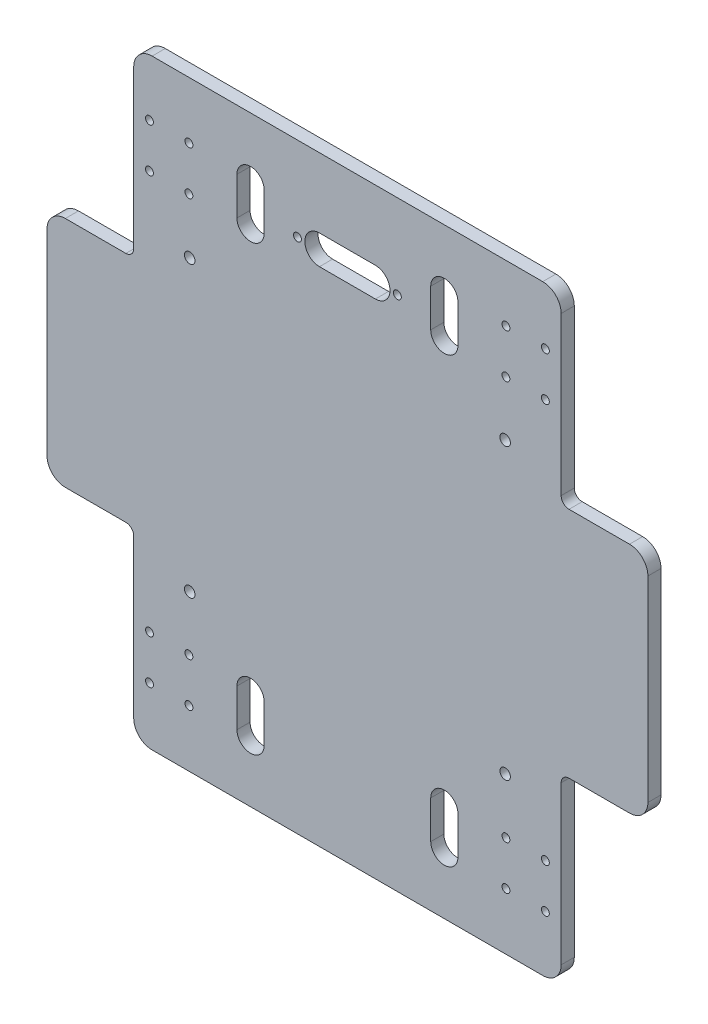
SolidWorks part; units mm, degrees
ref_plane "Front Plane" through (0, 0, 0) normal (0, 0, 1) x (1, 0, 0)
ref_plane "Top Plane" through (0, 0, 0) normal (0, 1, 0) x (1, 0, 0)
ref_plane "Right Plane" through (0, 0, 0) normal (1, 0, 0) x (0, 0, -1)
sketch "Sketch1" plane through (0, 0, 0) normal (0, 0, 1) x (1, 0, 0)
  line L0 (33, -6.6196) -> (39, -6.6196) construction
  line L1 (33, 0) -> (195.6, 0)
  line L2 (0, -70) -> (0, -158.6)
  line L3 (33, -228.6) -> (195.6, -228.6)
  line L4 (228.6, -70) -> (228.6, -158.6)
  line L5 (0, -70) -> (33, -70)
  line L6 (77.4385, -191.4014) -> (77.4385, -205.7986) construction
  line L11 (39, -30) -> (54, -30) construction
  line L12 (33, -70) -> (33, 0)
  line L13 (0, -158.6) -> (33, -158.6)
  line L14 (33, -158.6) -> (33, -228.6)
  line L15 (195.6, -158.6) -> (195.6, -228.6)
  line L16 (228.6, -158.6) -> (195.6, -158.6)
  line L17 (228.6, -70) -> (195.6, -70)
  line L18 (195.6, -70) -> (195.6, 0)
  line L19 (39, -30) -> (39, -38.375) construction
  line L20 (77.4385, -37.1986) -> (77.4385, -22.8014) construction
  line L21 (72.2648, -37.1986) -> (72.2648, -22.8014)
  line L22 (82.6122, -37.1986) -> (82.6122, -22.8014)
  line L23 (103.6573, -32) -> (124.9427, -32) construction
  line L24 (103.6573, -26.4466) -> (124.9427, -26.4466)
  line L25 (103.6573, -37.5534) -> (124.9427, -37.5534)
  line L26 (114.3, 0) -> (114.3, -14.4464) construction
  line L27 (0, -114.3) -> (33, -114.3) construction
  line L28 (72.2648, -191.4014) -> (72.2648, -205.7986)
  line L29 (82.6122, -191.4014) -> (82.6122, -205.7986)
  line L30 (151.1615, -191.4014) -> (151.1615, -205.7986) construction
  line L31 (156.3352, -191.4014) -> (156.3352, -205.7986)
  line L32 (145.9878, -191.4014) -> (145.9878, -205.7986)
  line L33 (151.1615, -37.1986) -> (151.1615, -22.8014) construction
  line L34 (156.3352, -37.1986) -> (156.3352, -22.8014)
  line L35 (145.9878, -37.1986) -> (145.9878, -22.8014)
  circle A0 centre (95.3, -32) radius 1.5
  circle A1 centre (133.3, -32) radius 1.5
  circle A2 centre (39, -21.625) radius 1.5
  circle A3 centre (39, -38.375) radius 1.5
  circle A4 centre (54, -38.375) radius 1.5
  circle A5 centre (54, -21.625) radius 1.5
  arc A6 (72.2648, -37.1986) -> (82.6122, -37.1986) centre (77.4385, -37.1986) ccw
  arc A7 (82.6122, -22.8014) -> (72.2648, -22.8014) centre (77.4385, -22.8014) ccw
  arc A8 (103.6573, -26.4466) -> (103.6573, -37.5534) centre (103.6573, -32) ccw
  arc A9 (124.9427, -37.5534) -> (124.9427, -26.4466) centre (124.9427, -32) ccw
  arc A10 (72.2648, -191.4014) -> (82.6122, -191.4014) centre (77.4385, -191.4014) cw
  arc A11 (82.6122, -205.7986) -> (72.2648, -205.7986) centre (77.4385, -205.7986) cw
  circle A12 centre (54, -206.975) radius 1.5
  circle A13 centre (54, -190.225) radius 1.5
  circle A14 centre (39, -190.225) radius 1.5
  circle A15 centre (39, -206.975) radius 1.5
  arc A16 (156.3352, -191.4014) -> (145.9878, -191.4014) centre (151.1615, -191.4014) ccw
  arc A17 (145.9878, -205.7986) -> (156.3352, -205.7986) centre (151.1615, -205.7986) ccw
  circle A18 centre (174.6, -190.225) radius 1.5
  circle A19 centre (174.6, -206.975) radius 1.5
  circle A20 centre (189.6, -206.975) radius 1.5
  circle A21 centre (189.6, -190.225) radius 1.5
  arc A22 (156.3352, -37.1986) -> (145.9878, -37.1986) centre (151.1615, -37.1986) cw
  arc A23 (145.9878, -22.8014) -> (156.3352, -22.8014) centre (151.1615, -22.8014) cw
  circle A24 centre (189.6, -38.375) radius 1.5
  circle A25 centre (174.6, -38.375) radius 1.5
  circle A26 centre (174.6, -21.625) radius 1.5
  circle A27 centre (189.6, -21.625) radius 1.5
  point P4 (114.3, -32)
  point P31 (77.4385, -30)
  point P37 (114.3, -32)
  point P49 (77.4385, -198.6)
  point P64 (151.1615, -198.6)
  point P79 (151.1615, -30)
  dimension "D2" = 15
  dimension "D3" = 16.75
  dimension "D1" = 70
  dimension "D4" = 33
extrude "Boss-Extrude1" add sketch "Sketch1" along normal blind 5
sketch "Sketch2" plane through (0, 0, 5) normal (0, 0, 1) x (1, 0, 0)
  line L0 (114.3, 0) -> (114.3, -59.3073) construction
  line L1 (195.6, 0) -> (33, 0) construction
  line L2 (114.3, -59.3073) -> (54.3, -59.3073) construction
  line L3 (114.3, -31.9409) -> (114.3, -212.7424) construction
  circle A0 centre (54.3, -59.3073) radius 2
  circle A1 centre (174.3, -59.3073) radius 2
  circle A2 centre (174.3, -169.2927) radius 2
  circle A3 centre (54.3, -169.2927) radius 2
  point P10 (174.3, -59.3073)
  point P18 (161.3502, -68.4042)
  dimension "D1" = 60
extrude "Cut-Extrude1" cut sketch "Sketch2" against normal blind 5
fillet "Fillet1" radius 7 6 edges at (0, -158.6, 2.5) (0, -70, 2.5) (228.6, -158.6, 2.5) (228.6, -70, 2.5) (195.6, 0, 2.5) (33, 0, 2.5)
fillet "Fillet2" radius 7 2 edges at (33, -228.6, 2.5) (195.6, -228.6, 2.5)
fillet "Fillet3" radius 3 4 edges at (195.6, -70, 2.5) (195.6, -158.6, 2.5) (33, -158.6, 2.5) (33, -70, 2.5)
